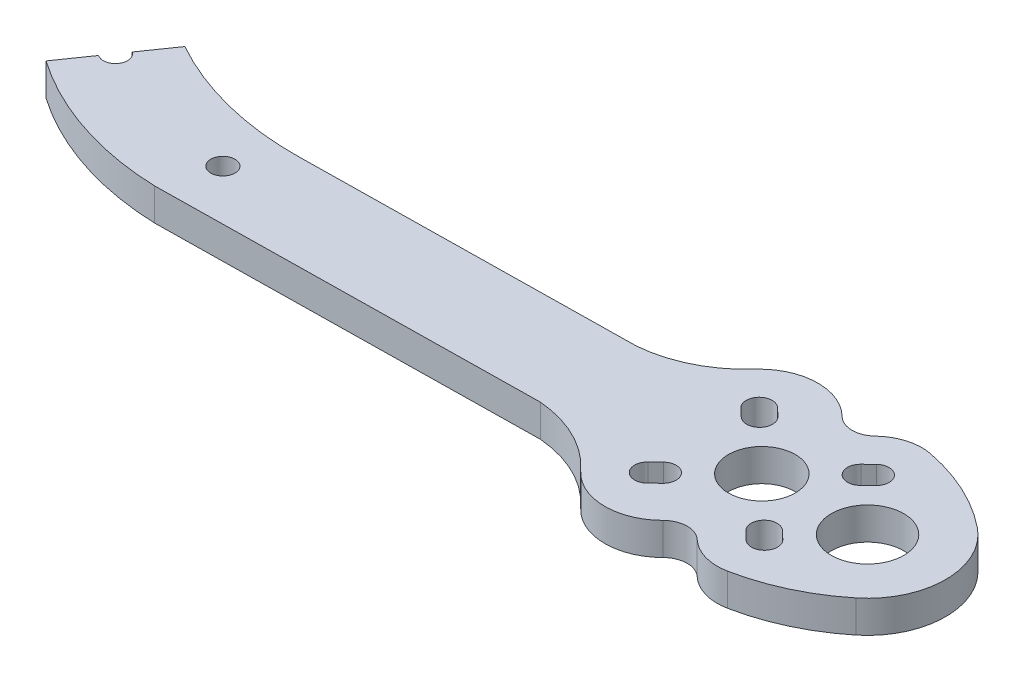
SolidWorks part; units mm, degrees
material "Thornel Mat VMA"
ref_plane "Front Plane" through (0, 0, 0) normal (0, 0, 1) x (1, 0, 0)
ref_plane "Top Plane" through (0, 0, 0) normal (0, 1, 0) x (1, 0, 0)
ref_plane "Right Plane" through (0, 0, 0) normal (1, 0, 0) x (0, 0, -1)
sketch "Sketch2" plane through (0, 0, 0) normal (0, 1, 0) x (1, 0, 0)
  line L0 (52.871, 39.224) -> (53.2096, 14.1062) construction
  dimension "D1" = 25.12
sketch "Sketch1" plane through (0, 0, 0) normal (0, 1, 0) x (1, 0, 0)
  line L0 (38.4281, 38.6258) -> (38.9445, 13.5111) construction
  line L1 (24.492, 26) -> (68.7851, 26.1) construction
  line L2 (24.492, 26) -> (24.492, 32) construction
  line L3 (24.492, 26) -> (24.5191, 20.0001) construction
  line L4 (24.492, 32) -> (-16.8236, 31.3893)
  line L5 (-22.6819, 19.3024) -> (24.5191, 20.0001)
  line L6 (-42.8745, 26) -> (-40.1931, 29.8538)
  line L7 (38.7289, 32.9791) -> (39.7179, 32.0344) construction
  line L8 (39.8418, 34.1443) -> (40.8309, 33.1997)
  line L9 (37.6159, 31.8138) -> (38.6049, 30.8691)
  line L10 (39.7179, 32.0344) -> (45.9851, 26.0485) construction
  line L13 (45.9851, 26.0485) -> (45.9615, 36.482) construction
  line L14 (53.2099, 33.0118) -> (52.2251, 32.0626) construction
  line L15 (52.0917, 34.172) -> (51.1069, 33.2229)
  line L16 (54.3281, 31.8515) -> (53.3434, 30.9024)
  line L17 (53.2413, 19.118) -> (52.2522, 20.0627) construction
  line L18 (52.1283, 17.9527) -> (51.1392, 18.8974)
  line L19 (54.3543, 20.2833) -> (53.3652, 21.2279)
  line L20 (38.7602, 19.0853) -> (39.745, 20.0344) construction
  line L21 (39.8785, 17.9251) -> (40.8632, 18.8742)
  line L22 (37.642, 20.2455) -> (38.6268, 21.1947)
  line L23 (68.7851, 26.1) -> (63.5851, 26.0781) construction
  line L24 (-38.4798, 32.3164) -> (-35.7984, 36.1702)
  circle A0 centre (59.0851, 26.0781) radius 4.5
  arc A1 (65.1909, 18.5409) -> (65.1568, 33.6428) centre (59.0851, 26.0781) ccw
  arc A2 (44.8153, 37.1899) -> (48.991, 37.1485) centre (46.9245, 39.3233) ccw
  arc A3 (54.2659, 38.6893) -> (48.991, 37.1485) centre (53.124, 32.7989) ccw
  arc A4 (44.8153, 37.1899) -> (34.3366, 36.8927) centre (39.7179, 32.0344) ccw
  arc A5 (24.492, 32) -> (34.3366, 36.8927) centre (23.2027, 46.9445) ccw
  arc A6 (65.1568, 33.6428) -> (54.2659, 38.6893) centre (49.5081, 14.1462) ccw
  arc A7 (49.5789, 24.1487) -> (54.6857, 25.1317) centre (53.1544, 19.3304) cw construction
  arc A8 (44.8656, 14.902) -> (49.0411, 14.9623) centre (46.9844, 12.7782) cw
  arc A9 (65.1909, 18.5409) -> (54.3228, 13.4453) centre (49.4543, 37.9666) cw
  arc A10 (35.6618, 26.0252) -> (43.8012, 26.0436) centre (39.745, 20.0344) cw construction
  arc A11 (24.5191, 20.0001) -> (34.3856, 15.1518) centre (23.2973, 5.0499) cw
  arc A12 (44.8656, 14.902) -> (34.3856, 15.1518) centre (39.745, 20.0344) cw
  arc A13 (54.3228, 13.4453) -> (49.0411, 14.9623) centre (53.1544, 19.3304) cw
  arc A14 (49.3851, 26.0562) -> (49.5789, 24.1487) centre (59.0851, 26.0781) ccw construction
  arc A16 (-35.7984, 36.1702) -> (-16.8236, 31.3893) centre (-17.4662, 68.8838) ccw
  arc A17 (-42.8745, 26) -> (-22.6819, 19.3024) centre (-21.4573, 56.7824) ccw
  arc A20 (39.8418, 34.1443) -> (37.6159, 31.8138) centre (38.7289, 32.9791) ccw
  arc A21 (38.6049, 30.8691) -> (40.8309, 33.1997) centre (39.7179, 32.0344) ccw
  circle A22 centre (45.9851, 26.0485) radius 4.15
  arc A23 (52.0917, 34.172) -> (54.3281, 31.8515) centre (53.2099, 33.0118) cw
  arc A24 (53.3434, 30.9024) -> (51.1069, 33.2229) centre (52.2251, 32.0626) cw
  arc A25 (52.1283, 17.9527) -> (54.3543, 20.2833) centre (53.2413, 19.118) ccw
  arc A26 (53.3652, 21.2279) -> (51.1392, 18.8974) centre (52.2522, 20.0627) ccw
  arc A27 (39.8785, 17.9251) -> (37.642, 20.2455) centre (38.7602, 19.0853) cw
  arc A28 (38.6268, 21.1947) -> (40.8632, 18.8742) centre (39.745, 20.0344) cw
  arc A29 (-40.1931, 29.8538) -> (-38.4798, 32.3164) centre (-39.3364, 31.0851) ccw
  circle A30 centre (-20.5702, 25.6652) radius 1.5
  point P41 (39.2234, 32.5067)
  point P51 (52.7175, 32.5372)
  point P60 (52.7467, 19.5903)
  point P66 (39.2526, 19.5599)
  dimension "D5" = 9
  dimension "D7" = 12
  dimension "D10" = 6
  dimension "D12" = 14.5
  dimension "D15" = 30
  dimension "D16" = 50
  dimension "D17" = 8.3
  dimension "D19" = 75
  dimension "D20" = 75
  dimension "D28" = 1.6114
  dimension "D29" = 13.1
  dimension "D31" = 3
  dimension "D18" = 0.9394
  dimension "D30" = 3
  dimension "D1" = 44.293
  dimension "D2" = 24.492
  dimension "D3" = 26
  dimension "D4" = 0.1
  dimension "D6" = 5.2
  dimension "D8" = 13.2726
  dimension "D9" = 21.8606
  dimension "D11" = 6.7343
  dimension "D13" = 6
  dimension "D14" = 6
  dimension "D21" = 41.3157
  dimension "D22" = 47.201
  dimension "D23" = 12.3896
  dimension "D24" = 0.6977
  dimension "D25" = 1.2246
  dimension "D26" = 5.2157
  dimension "D27" = 1.3677
extrude "Boss-Extrude2" add sketch "Sketch1" along normal blind 4 contours A30
ref_plane "Plane2" through (47.0131, 0, -0.1061) normal (-1, 0, 0.0023) x (0.0023, 0, 1)
